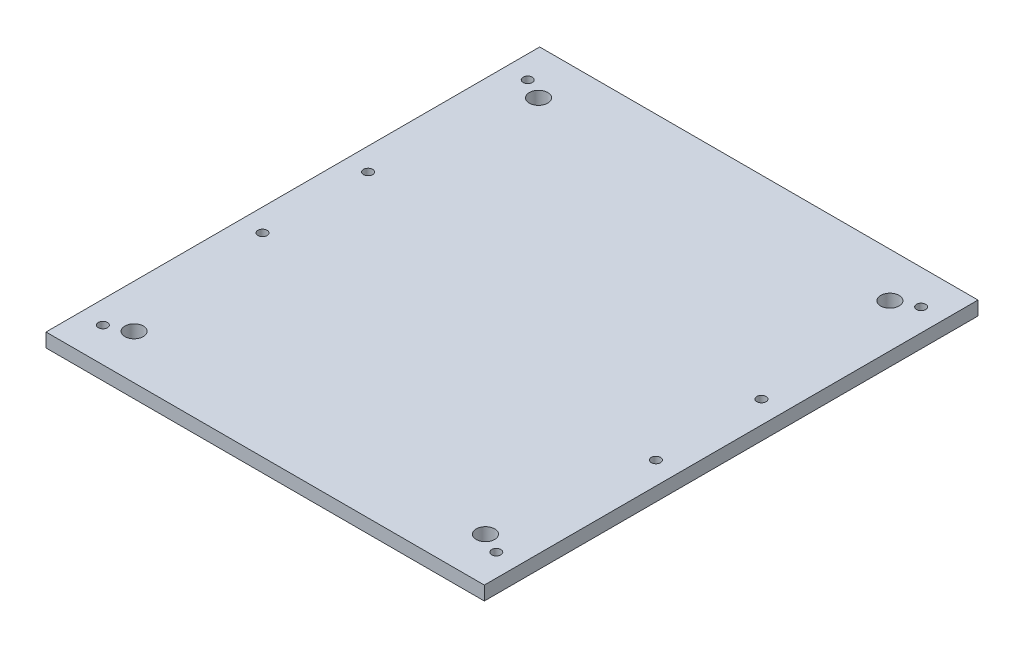
SolidWorks part; units mm, degrees
ref_plane "Front Plane" through (0, 0, 0) normal (0, 0, 1) x (1, 0, 0)
ref_plane "Top Plane" through (0, 0, 0) normal (0, 1, 0) x (1, 0, 0)
ref_plane "Right Plane" through (0, 0, 0) normal (1, 0, 0) x (0, 0, -1)
sketch "Sketch2" plane through (0, 0, 0) normal (0, 1, 0) x (1, 0, 0)
  line L1 (-47.5, -53.5) -> (47.5, -53.5)
  line L2 (-47.5, -53.5) -> (-47.5, 53.5)
  line L3 (-47.5, 53.5) -> (47.5, 53.5)
  line L4 (47.5, -53.5) -> (47.5, 53.5)
  line L5 (-47.5, -53.5) -> (47.5, 53.5) construction
  line L6 (-47.5, 53.5) -> (47.5, -53.5) construction
  line L8 (-55, 0) -> (55, 0) construction
  line L9 (0, -55) -> (0, 55) construction
  line L15 (-60, 66) -> (60, 66)
  line L16 (-60, 66) -> (-60, -66)
  line L17 (-60, -66) -> (60, -66)
  line L18 (60, 66) -> (60, -66)
  line L19 (-60, 66) -> (60, -66) construction
  line L20 (-60, -66) -> (60, 66) construction
  circle A1 centre (38.075, -43.825) radius 2
  circle A2 centre (38.075, 43.825) radius 2
  circle A3 centre (-38.075, -43.825) radius 2
  circle A4 centre (-38.075, 43.825) radius 2
  point P0 (0, 0)
  point P20 (0, 0)
  point P21 (0, 0)
  dimension "D3" = 87.65
  dimension "D5" = 4
  dimension "D4" = 76.15
  dimension "D1" = 95
  dimension "D2" = 107
  dimension "D6" = 120
  dimension "D7" = 132
extrude "Boss-Extrude1" add sketch "Sketch2" along normal blind 3
sketch "Sketch3" plane through (0, 3, 0) normal (0, 1, 0) x (1, 0, 0)
  line L5 (-47.515, 40.2371) -> (-32.4121, 40.2371) construction
  line L6 (-47.5, -53.5) -> (-47.5, 53.5) construction
  line L10 (-47.5, 17.2402) -> (-47.5, 40.2371)
  line L11 (-47.6, 40.3371) -> (-32.2822, 40.3371)
  line L12 (-32.2822, 40.3371) -> (-30.49, 37.2328)
  line L13 (-30.49, 17.1402) -> (-30.49, 37.2328)
  line L14 (-47.6, 17.1402) -> (-30.49, 17.1402)
  line L15 (-47.6, 17.1402) -> (-47.6, 40.3371)
  line L16 (-47.5, 40.2371) -> (-32.34, 40.2371) construction
  line L17 (-47.5, 17.2402) -> (-30.59, 17.2402) construction
  line L18 (-30.59, 17.2402) -> (-30.59, 37.206) construction
  line L19 (-32.34, 40.2371) -> (-30.59, 37.206) construction
  line L20 (0, 62.7045) -> (0, 59.4045) construction
  line L21 (32.2822, 40.3371) -> (30.49, 37.2328)
  line L22 (30.49, 17.1402) -> (30.49, 37.2328)
  line L23 (47.6, 17.1402) -> (30.49, 17.1402)
  line L24 (47.5, 17.2402) -> (47.5, 40.2371)
  line L25 (47.6, 40.3371) -> (32.2822, 40.3371)
  line L26 (-130.0965, 0) -> (-126.7965, 0) construction
  line L27 (47.5, -17.2402) -> (47.5, -40.2371)
  line L28 (47.6, -17.1402) -> (30.49, -17.1402)
  line L29 (30.49, -17.1402) -> (30.49, -37.2328)
  line L30 (32.2822, -40.3371) -> (30.49, -37.2328)
  line L31 (47.6, -40.3371) -> (32.2822, -40.3371)
  line L32 (-30.49, -17.1402) -> (-30.49, -37.2328)
  line L33 (-32.2822, -40.3371) -> (-30.49, -37.2328)
  line L34 (-47.6, -40.3371) -> (-32.2822, -40.3371)
  line L35 (-47.5, -17.2402) -> (-47.5, -40.2371)
  line L36 (-47.6, -17.1402) -> (-30.49, -17.1402)
  dimension "D1" = 0.1
sketch "Sketch6" plane through (0, 3, 0) normal (0, 1, 0) x (1, 0, 0)
  line L24 (-47.5, 53.5) -> (-47.5, -53.5)
  line L30 (-47.5, -53.5) -> (47.5, -53.5)
  line L31 (47.5, -53.5) -> (47.5, 53.5)
  line L42 (47.5, 53.5) -> (-47.5, 53.5)
  line L48 (-47.5, 53.5) -> (-47.5, -53.5)
  line L54 (-47.5, -53.5) -> (47.5, -53.5)
  line L55 (47.5, -53.5) -> (47.5, 53.5)
  line L66 (47.5, 53.5) -> (-47.5, 53.5)
  dimension "D1" = 0
sketch "Sketch7" plane through (0, 3, 0) normal (0, 1, 0) x (1, 0, 0)
  line L1 (47.5, 53.5) -> (-47.5, 53.5) construction
  line L2 (47.6, 40.3371) -> (32.2822, 40.3371) construction
  circle A0 centre (42.63, 46.04) radius 1
  dimension "D3" = 2
  dimension "D1" = 5.7029
  dimension "D2" = 7.46
extrude "Cut-Extrude2" cut sketch "Sketch7" against normal blind 10
sketch "Sketch9" plane through (0, 3, 0) normal (0, 1, 0) x (1, 0, 0)
  line L0 (47.5, 28.7386) -> (10.5585, 28.7386)
  line L1 (47.5, 17.2402) -> (47.5, 40.2371) construction
ref_plane "Plane1" through (0, 0, -28.7386) normal (0, 0, -1) x (-1, 0, 0)
mirror "Mirror2" about plane through (0, 0, -28.7386) normal (0, 0, -1) of "Cut-Extrude2"
mirror "Mirror3" about plane through (0, 0, 0) normal (1, 0, 0) of "Cut-Extrude2", "Mirror2" second plane through (0, 0, 0) second plane normal (0, 0, 1)
